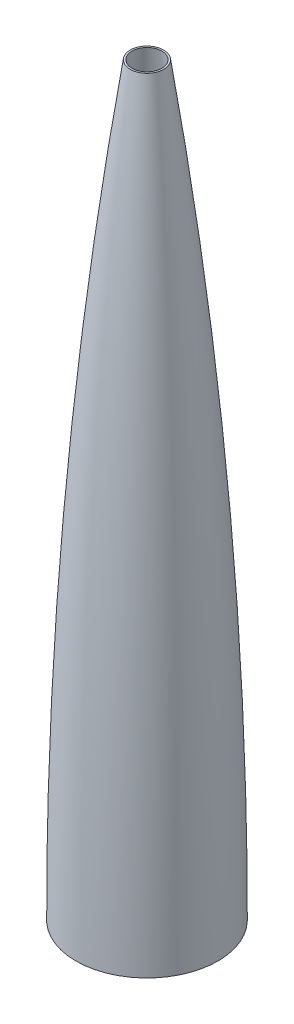
SolidWorks part; units mm, degrees
material "A-Glass Fiber"
ref_plane "Front Plane" through (0, 0, 0) normal (0, 0, 1) x (1, 0, 0)
ref_plane "Top Plane" through (0, 0, 0) normal (0, 1, 0) x (1, 0, 0)
ref_plane "Right Plane" through (0, 0, 0) normal (1, 0, 0) x (0, 0, -1)
sketch "Sketch1" plane through (0, 0, 0) normal (0, 0, 1) x (1, 0, 0)
  line L0 (0, 0) -> (-49.53, 0) construction
  line L1 (-49.53, 0) -> (-50.8, 0)
  line L2 (-50.8, -33.7223) -> (-50.8, 0) construction
  line L3 (0, 609.6) -> (0, 0) construction
  line L6 (-10.6863, 533.4) -> (-11.9698, 533.4)
  line L7 (-10.6863, 533.4) -> (0, 533.4) construction
  arc A0 (-50.8, 0) -> (0, 609.6) centre (3632.2, 0) cw construction
  arc A1 (-49.53, 0) -> (0, 601.8795) centre (3632.2, 0) cw construction
  arc A6 (-11.9698, 533.4) -> (-50.8, 0) centre (3632.2, 0) ccw
  arc A7 (-10.6863, 533.4) -> (-49.53, 0) centre (3632.2, 0) ccw
  dimension "D1" = 50.8
  dimension "D2" = 49.53
  dimension "D3" = 609.6
  dimension "D4" = 76.2
revolve "Revolve3" add sketch "Sketch1" angle 360 about L3
sketch "Sketch3" plane through (0, 0, 0) normal (0, 0, 1) x (1, 0, 0)
  line L0 (0, 0) -> (-49.53, 0) construction
  line L1 (-49.53, 0) -> (-50.8, 0)
  line L2 (-50.8, -33.7223) -> (-50.8, 0) construction
  line L3 (0, 609.6) -> (0, 0) construction
  line L7 (-11.9698, 533.4) -> (0, 533.4)
  line L8 (10.6863, 533.4) -> (-10.6863, 533.4) construction
  line L9 (0, 533.4) -> (0, 609.6)
  arc A0 (-50.8, 0) -> (0, 609.6) centre (3632.2, 0) cw construction
  arc A8 (-11.9698, 533.4) -> (0, 609.6) centre (3632.2, 0) cw
  dimension "D1" = 50.8
  dimension "D2" = 49.53
  dimension "D3" = 609.6
